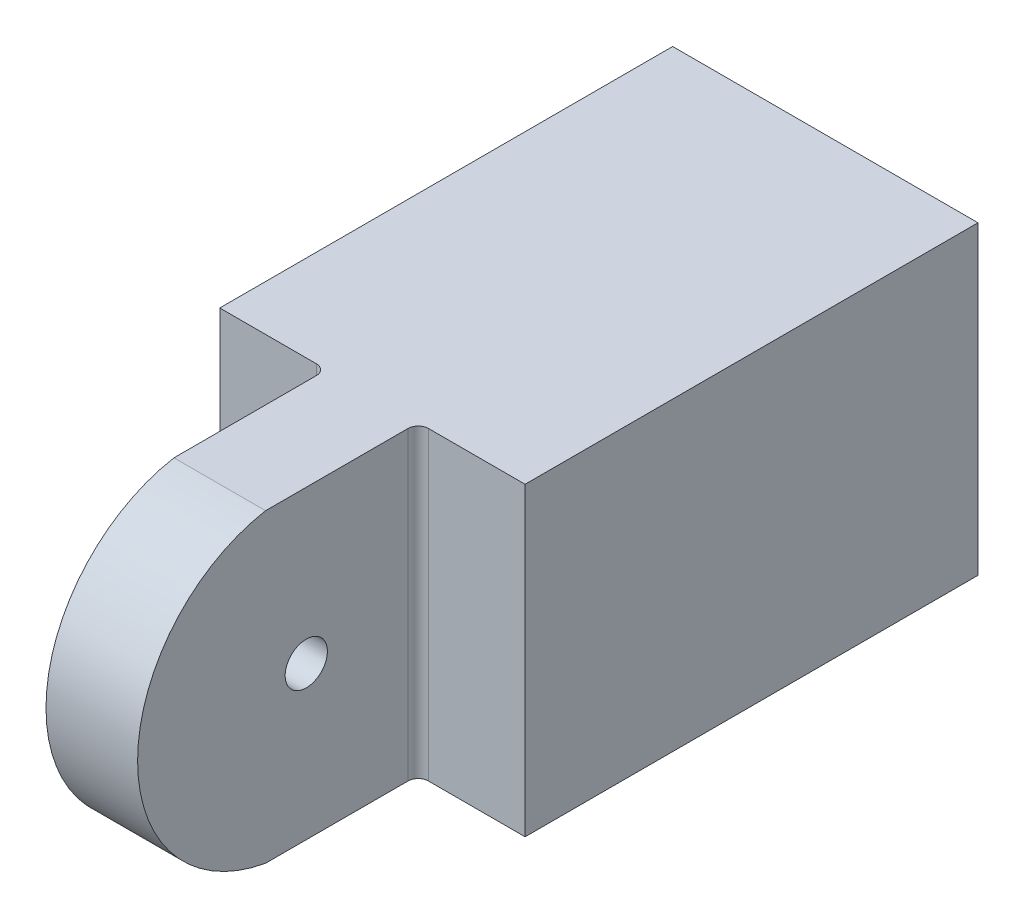
SolidWorks part; units mm, degrees
ref_plane "Front Plane" through (0, 0, 0) normal (0, 0, 1) x (1, 0, 0)
ref_plane "Top Plane" through (0, 0, 0) normal (0, 1, 0) x (1, 0, 0)
ref_plane "Right Plane" through (0, 0, 0) normal (1, 0, 0) x (0, 0, -1)
sketch "Sketch2" plane through (0, 0, 0) normal (0, 0, 1) x (1, 0, 0)
  line L1 (-30, 30) -> (30, 30)
  line L2 (-30, 30) -> (-30, -30)
  line L3 (-30, -30) -> (30, -30)
  line L4 (30, 30) -> (30, -30)
  line L5 (-30, 30) -> (30, -30) construction
  line L6 (-30, -30) -> (30, 30) construction
  point P0 (0, 0)
  dimension "D1" = 60
  dimension "D2" = 60
extrude "Boss-Extrude1" add sketch "Sketch2" along normal blind 89
ref_plane "Plane1" through (0, 0, 89) normal (0, 0, 1) x (1, 0, 0)
sketch "Sketch3" plane through (0, 0, 89) normal (0, 0, 1) x (1, 0, 0)
  line L0 (30, 30) -> (-30, 30) construction
  line L1 (9, -30) -> (-9, -30)
  line L2 (9, -30) -> (9, 30)
  line L3 (9, 30) -> (-9, 30)
  line L4 (-9, -30) -> (-9, 30)
  line L5 (9, -30) -> (-9, 30) construction
  line L6 (9, 30) -> (-9, -30) construction
  point P0 (0, 0)
  dimension "D1" = 18
extrude "Boss-Extrude2" add sketch "Sketch3" along normal blind 30
ref_plane "Plane2" through (9, 0, 0) normal (1, 0, 0) x (0, 0, -1)
sketch "Sketch4" plane through (9, 0, 0) normal (1, 0, 0) x (0, 0, -1)
  line L0 (-119, -30) -> (-119, 30)
  arc A0 (-119, -30) -> (-119, 30) centre (-113.6759, 0) cw
extrude "Boss-Extrude3" add sketch "Sketch4" against normal blind 18
fillet "Fillet1" radius 2 2 edges at (9, 0, 89) (-9, 0, 89)
ref_plane "Plane4" through (0, 0, 0) normal (0, 0, -1) x (-1, 0, 0)
sketch "Sketch7" plane through (0, 0, 0) normal (0, 0, -1) x (-1, 0, 0)
  line L0 (30, 30) -> (30, -30) construction
  line L1 (-25, 25) -> (25, 25)
  line L2 (-25, 25) -> (-25, -25)
  line L3 (-25, -25) -> (25, -25)
  line L4 (25, 25) -> (25, -25)
  line L5 (-25, 25) -> (25, -25) construction
  line L6 (-25, -25) -> (25, 25) construction
  line L7 (-30, 30) -> (30, 30) construction
  point P0 (0, 0)
  dimension "D1" = 5
  dimension "D2" = 5
extrude "Cut-Extrude1" cut sketch "Sketch7" against normal blind 81 contours L4 L3 L2 L1
ref_plane "Plane5" through (-9, 0, 0) normal (-1, 0, 0) x (0, 0, 1)
sketch "Sketch8" plane through (-9, 0, 0) normal (-1, 0, 0) x (0, 0, 1)
  line L0 (91, 30) -> (91, -30) construction
  circle A0 centre (111, 0) radius 4.15
  point P2 (112.9237, 0)
  point P3 (117.5528, 0)
  dimension "D1" = 8.3
  dimension "D2" = 20
extrude "Cut-Extrude2" cut sketch "Sketch8" against normal through all
